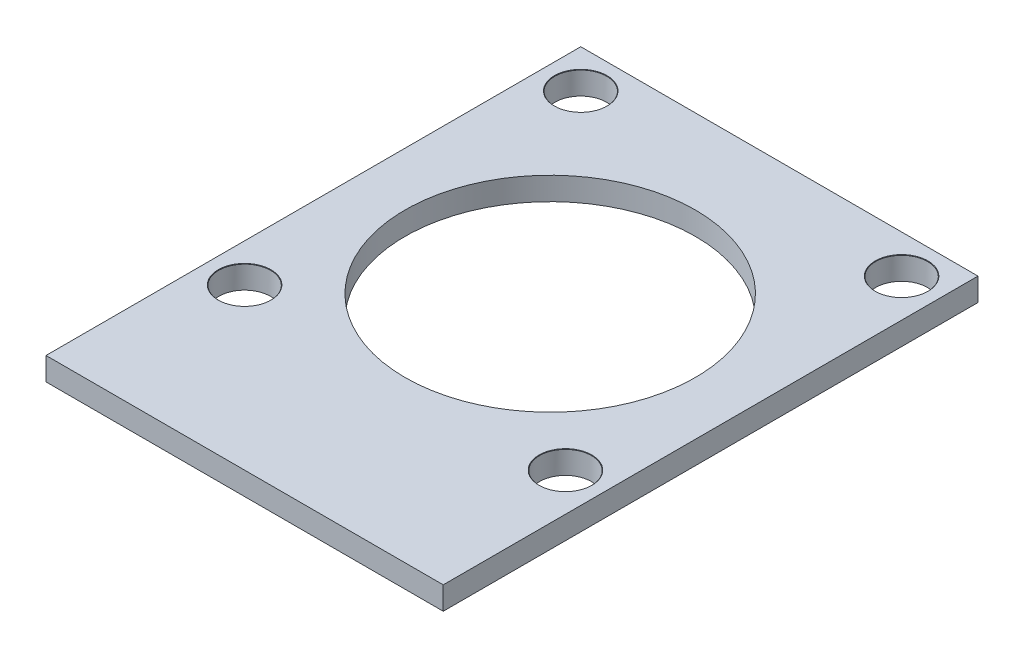
SolidWorks part; units mm, degrees
ref_plane "Front Plane" through (0, 0, 0) normal (0, 0, 1) x (1, 0, 0)
ref_plane "Top Plane" through (0, 0, 0) normal (0, 1, 0) x (1, 0, 0)
ref_plane "Right Plane" through (0, 0, 0) normal (1, 0, 0) x (0, 0, -1)
sketch "Sketch1" plane through (0, 0, 0) normal (0, 1, 0) x (1, 0, 0)
  line L1 (0, 0) -> (26, 0)
  line L2 (0, 0) -> (0, 35)
  line L3 (0, 35) -> (26, 35)
  line L4 (26, 0) -> (26, 35)
  dimension "D1" = 35
  dimension "D2" = 26
extrude "Boss-Extrude1" add sketch "Sketch1" along normal blind 1.5
hole_wizard "M3 Clearance Hole1" positions "Sketch2" profile "Sketch3" hole size "M3" standard "ANSI Metric"
sketch "Sketch2" plane through (0, 1.5, 0) normal (0, 1, 0) x (1, 0, 0)
  line L0 (0, 35) -> (0, 0) construction
  line L1 (26, 35) -> (0, 35) construction
  line L3 (26, 0) -> (26, 35) construction
  point P0 (2.5, 32.5)
  point P2 (2.5, 10.5)
  point P4 (23.5, 10.5)
  point P6 (23.5, 32.5)
  dimension "D1" = 2.5
  dimension "D2" = 2.5
  dimension "D3" = 2.5
  dimension "D6" = 2.5
  dimension "D7" = 2.5
  dimension "D8" = 2.5
  dimension "D10" = 21
  dimension "D4" = 22
  dimension "D5" = 22
sketch "Sketch3" plane through (2.5, 1.5, -32.5) normal (1, 0, 0) x (0, 0, 1)
  line L0 (0, 0) -> (0, 3)
  line L1 (0, 3) -> (1.7, 3)
  line L2 (1.7, 3) -> (1.7, 0.025)
  line L3 (1.7, 0.025) -> (1.725, 0)
  line L5 (1.725, 0) -> (0, 0)
  line L6 (-1.7, 0.025) -> (-1.725, 0) construction
  line L10 (0, 3) -> (-1.7, 3) construction
  line L11 (0, -6.35) -> (0, 107.95) construction
  dimension "Hole Dia." = 3.4
  dimension "Hole Depth" = 3
  dimension "Near C'Sink Dia." = 3.45
  dimension "Near C'Sink Angle" = 90
  dimension "Drill Angle" = 180
sketch "Sketch4" plane through (0, 1.5, 0) normal (0, 1, 0) x (1, 0, 0)
  line L0 (0, 35) -> (0, 0) construction
  line L1 (0, 0) -> (26, 0) construction
  circle A0 centre (13, 20) radius 9.5
  dimension "D1" = 19
  dimension "D2" = 13
  dimension "D3" = 20
extrude "Cut-Extrude1" cut sketch "Sketch4" against normal through all
equation "\"D2@Sketch2\"=\"D1@Sketch2\""
equation "\"D3@Sketch2\"=\"D1@Sketch2\""
equation "\"D6@Sketch2\"=\"D1@Sketch2\""
equation "\"D7@Sketch2\"=\"D1@Sketch2\""
equation "\"D8@Sketch2\"=\"D1@Sketch2\""
